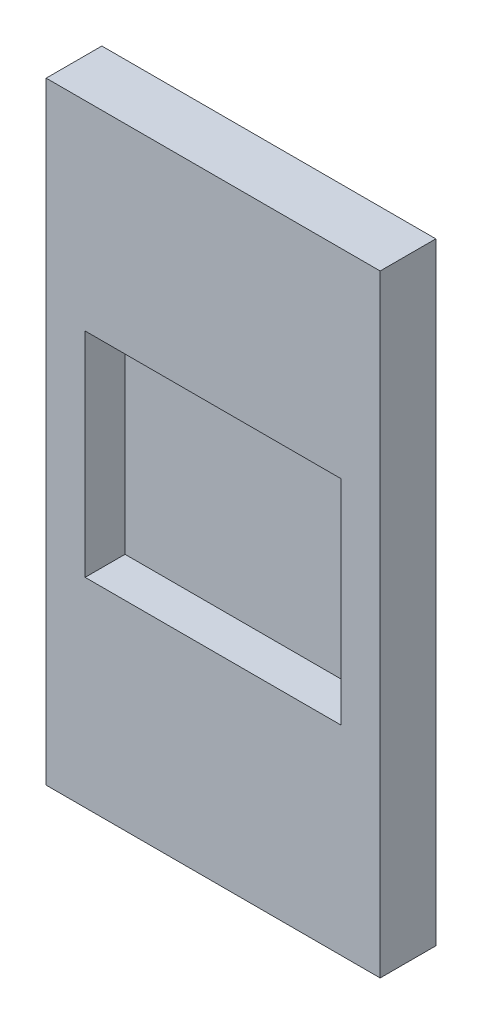
SolidWorks part; units mm, degrees
ref_plane "정면" through (0, 0, 0) normal (0, 0, 1) x (1, 0, 0)
ref_plane "윗면" through (0, 0, 0) normal (0, 1, 0) x (1, 0, 0)
ref_plane "우측면" through (0, 0, 0) normal (1, 0, 0) x (0, 0, -1)
sketch "스케치1" plane through (0, 0, 0) normal (0, 0, 1) x (1, 0, 0)
  line L1 (-9, -16.5) -> (9, -16.5)
  line L2 (-9, -16.5) -> (-9, 16.5)
  line L3 (-9, 16.5) -> (9, 16.5)
  line L4 (9, -16.5) -> (9, 16.5)
  line L5 (-9, -16.5) -> (9, 16.5) construction
  line L6 (-9, 16.5) -> (9, -16.5) construction
  point P0 (0, 0)
  dimension "D1" = 18
  dimension "D2" = 33
extrude "보스-돌출1" add sketch "스케치1" along normal blind 3
sketch "스케치2" plane through (0, 0, 3) normal (0, 0, 1) x (1, 0, 0)
  line L1 (-6.9, -5.75) -> (6.9, -5.75)
  line L2 (-6.9, -5.75) -> (-6.9, 5.75)
  line L3 (-6.9, 5.75) -> (6.9, 5.75)
  line L4 (6.9, -5.75) -> (6.9, 5.75)
  line L5 (-6.9, -5.75) -> (6.9, 5.75) construction
  line L6 (-6.9, 5.75) -> (6.9, -5.75) construction
  point P1 (0, 0)
  dimension "D1" = 13.8
  dimension "D2" = 11.5
extrude "컷-돌출1" cut sketch "스케치2" against normal blind 2.15
